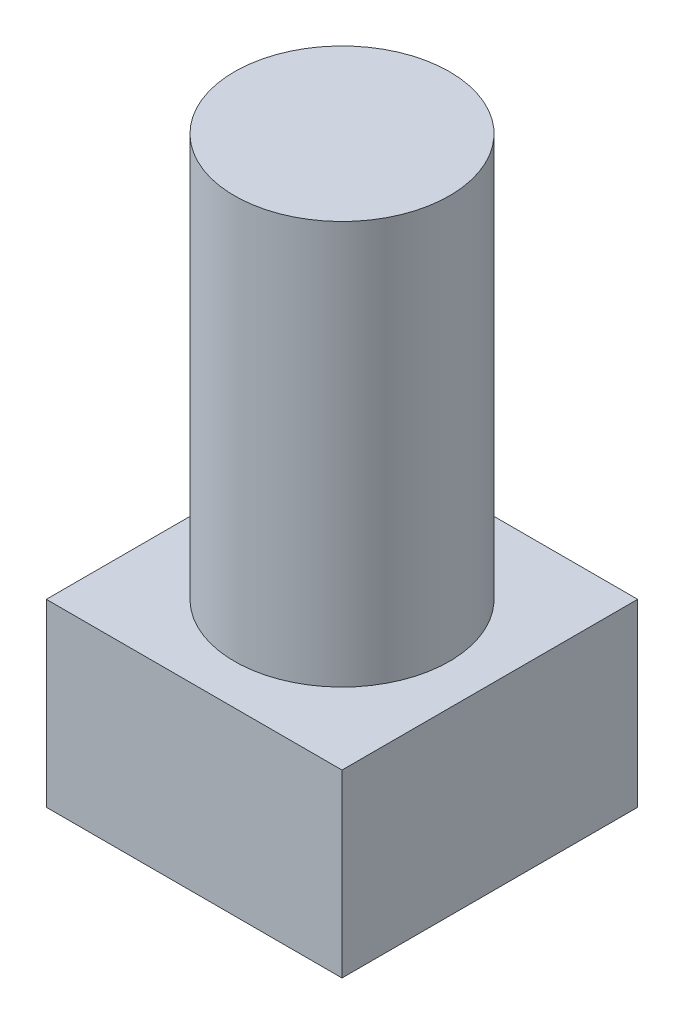
SolidWorks part; units mm, degrees
ref_plane "Plan de face" through (0, 0, 0) normal (0, 0, 1) x (1, 0, 0)
ref_plane "Plan de dessus" through (0, 0, 0) normal (0, 1, 0) x (1, 0, 0)
ref_plane "Plan de droite" through (0, 0, 0) normal (1, 0, 0) x (0, 0, -1)
sketch "Esquisse1" plane through (0, 0, 0) normal (0, 0, 1) x (1, 0, 0)
  line L0 (0, 0) -> (0, 22.5546) construction
  line L1 (0, 0) -> (8, 0)
  line L2 (8, 0) -> (8, 6.7)
  line L3 (8, 6.7) -> (4, 6.7)
  line L4 (4, 6.7) -> (4, 21.7)
  line L5 (4, 21.7) -> (0, 21.7)
  line L6 (0, 0) -> (0, 21.7)
  dimension "D1" = 8
  dimension "D2" = 15
  dimension "D3" = 16
  dimension "D4" = 6.7
revolve "Révolution1" add sketch "Esquisse1" angle 360 about L0
sketch "Esquisse2" plane through (0, 0, 0) normal (0, -1, 0) x (1, 0, 0)
  line L1 (-5.5, -5.5) -> (5.5, -5.5)
  line L2 (-5.5, -5.5) -> (-5.5, 5.5)
  line L3 (-5.5, 5.5) -> (5.5, 5.5)
  line L4 (5.5, -5.5) -> (5.5, 5.5)
  line L5 (-5.5, -5.5) -> (5.5, 5.5) construction
  line L6 (-5.5, 5.5) -> (5.5, -5.5) construction
  point P0 (0, 0)
  dimension "D1" = 11
  dimension "D2" = 11
extrude "Enlèv. mat.-Extru.1" cut sketch "Esquisse2" against normal through all flip side to cut
hole_wizard "Trou taraudé M41" positions "Esquisse4" profile "Esquisse3" tap size "M4" standard "ISO"
sketch "Esquisse4" plane through (0, 0, 0) normal (0, -1, 0) x (1, 0, 0)
  point P0 (0, 0)
sketch "Esquisse3" plane through (0, 0, 0) normal (1, 0, 0) x (0, 0, -1)
  line L0 (0, 0) -> (0, 9.9914)
  line L1 (0, 9.9914) -> (1.65, 9)
  line L2 (1.65, 9) -> (1.65, 0)
  line L5 (1.65, 0) -> (0, 0)
  line L10 (0, 9.9914) -> (-1.65, 9) construction
  line L11 (0, -6.35) -> (0, 107.95) construction
  dimension "Diamètre du trou pour taraudage" = 3.3
  dimension "Profondeur du trou pour taraudage" = 9
  dimension "Angle de pointe" = 118
cosmetic thread "Filetage de perçage1" parameters "D1"=7, "D2"=4
